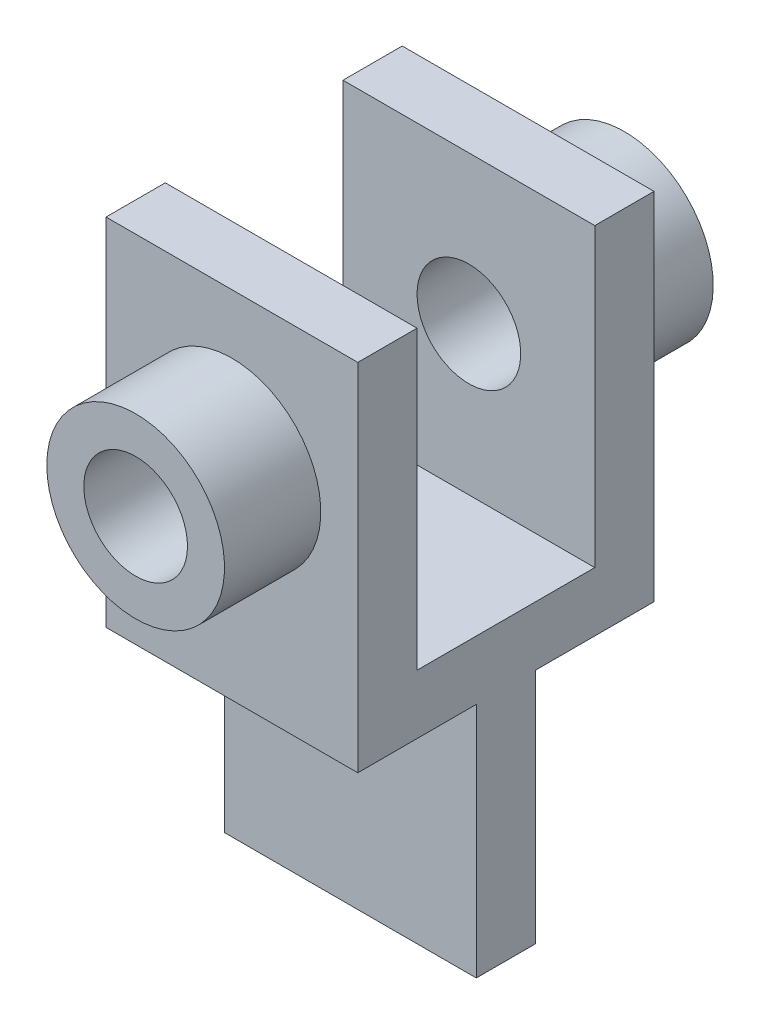
SolidWorks part; units mm, degrees
ref_plane "Front Plane" through (0, 0, 0) normal (0, 0, 1) x (1, 0, 0)
ref_plane "Top Plane" through (0, 0, 0) normal (0, 1, 0) x (1, 0, 0)
ref_plane "Right Plane" through (0, 0, 0) normal (1, 0, 0) x (0, 0, -1)
sketch "Croquis1" plane through (0, 0, 0) normal (1, 0, 0) x (0, 0, -1)
  line L0 (0, 0) -> (0, 32)
  line L1 (0, 32) -> (-16, 32)
  line L2 (-16, 32) -> (-16, 80)
  line L3 (-16, 80) -> (-8, 80)
  line L4 (-8, 80) -> (-8, 40)
  line L5 (-8, 40) -> (16, 40)
  line L6 (16, 40) -> (16, 80)
  line L7 (16, 80) -> (24, 80)
  line L8 (24, 80) -> (24, 32)
  line L9 (24, 32) -> (8, 32)
  line L10 (8, 32) -> (8, 0)
  line L11 (8, 0) -> (0, 0)
  dimension "D1" = 8
  dimension "D2" = 8
  dimension "D3" = 8
  dimension "D4" = 8
  dimension "D5" = 16
  dimension "D6" = 16
  dimension "D7" = 48
  dimension "D8" = 48
  dimension "D9" = 80
extrude "Saliente-Extruir1" add sketch "Croquis1" along normal mid plane 34
sketch "Croquis10" plane through (0, 0, 16) normal (0, 0, 1) x (1, 0, 0)
  line L0 (0, 80) -> (0, 40) construction
  line L1 (17, 80) -> (-17, 80) construction
  circle A0 centre (0, 60) radius 7
  dimension "D2" = 14
  dimension "D1" = 40
extrude "Cortar-Extruir2" cut sketch "Croquis10" against normal through all
sketch "Croquis11" plane through (0, 0, 16) normal (0, 0, 1) x (1, 0, 0)
  circle A0 centre (0, 60) radius 12
  circle A1 centre (0, 60) radius 7
  dimension "D1" = 24
extrude "Saliente-Extruir5" add sketch "Croquis11" along normal blind 13
sketch "Croquis12" plane through (0, 0, -24) normal (0, 0, -1) x (-1, 0, 0)
  circle A0 centre (0, 60) radius 12
  circle A1 centre (0, 60) radius 7
  dimension "D1" = 24
extrude "Saliente-Extruir6" add sketch "Croquis12" along normal blind 13
